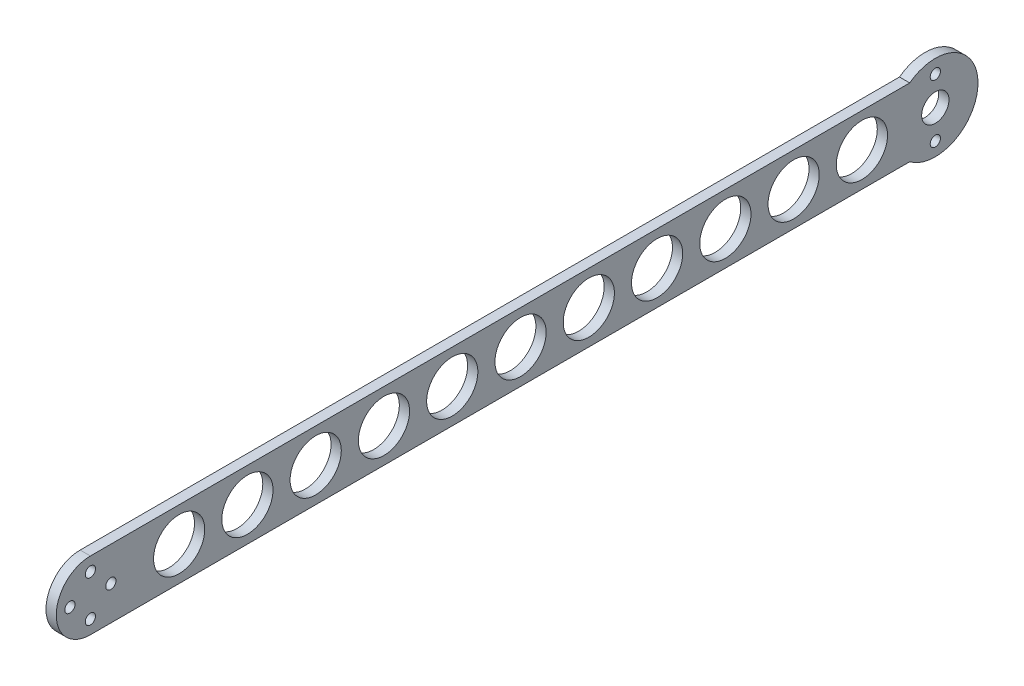
SolidWorks part; units mm, degrees
ref_plane "前视基准面" through (0, 0, 0) normal (0, 0, 1) x (1, 0, 0)
ref_plane "上视基准面" through (0, 0, 0) normal (0, 1, 0) x (1, 0, 0)
ref_plane "右视基准面" through (0, 0, 0) normal (1, 0, 0) x (0, 0, -1)
other "Configuration Table"
sketch "草图1" plane through (0, 0, 0) normal (1, 0, 0) x (0, 0, -1)
  line L5 (-120, 10) -> (120, 10)
  line L7 (-120, -10) -> (120, -10)
  line L9 (0, -10) -> (0, 10) construction
  line L10 (-120, 0) -> (127.5, 0) construction
  arc A1 (120, -10) -> (120, 10) centre (127.5, 0) ccw
  arc A2 (-120, 10) -> (-120, -10) centre (-120, 0) ccw
  point P0 (0, 0)
  point P1 (0, 0)
  point P5 (0, 0)
  dimension "D4" = 20
  dimension "D3" = 25
  dimension "D1" = 240
  dimension "D2" = 20
extrude "凸台-拉伸1" add sketch "草图1" along normal blind 3
sketch "草图2" plane through (3, 0, 0) normal (1, 0, 0) x (0, 0, -1)
  line L0 (120, 10) -> (-120, 10) construction
  circle A0 centre (-120, 0) radius 6 construction
  circle A1 centre (-120, 6) radius 1.5
  circle A2 centre (-114, 0) radius 1.5
  circle A3 centre (-120, -6) radius 1.5
  circle A4 centre (-126, 0) radius 1.5
  circle A5 centre (127.5, 0) radius 8.5 construction
  circle A7 centre (127.5, 8.5) radius 1.5
  circle A8 centre (127.5, -8.5) radius 1.5
  circle A9 centre (127.5, 0) radius 4
  dimension "D2" = 12
  dimension "D4" = 3
  dimension "D5" = 3
  dimension "D6" = 3
  dimension "D7" = 3
  dimension "D8" = 17
  dimension "D9" = 3
  dimension "D10" = 3
  dimension "D11" = 8
  dimension "D1" = 120
  dimension "D3" = 10
extrude "切除-拉伸1" cut sketch "草图2" against normal blind 3
sketch "草图4" plane through (3, 0, 0) normal (1, 0, 0) x (0, 0, -1)
  line L0 (120, 10) -> (-120, 10) construction
  circle A0 centre (-94, 0) radius 7.5
  circle A1 centre (-114, 0) radius 1.5 construction
  circle A2 centre (-74, 0) radius 7.5 construction
  circle A3 centre (-74, 0) radius 7.5
  circle A4 centre (-54, 0) radius 7.5
  circle A5 centre (-34, 0) radius 7.5
  circle A6 centre (-14, 0) radius 7.5
  circle A7 centre (6, 0) radius 7.5
  circle A8 centre (26, 0) radius 7.5
  circle A9 centre (46, 0) radius 7.5
  circle A10 centre (66, 0) radius 7.5
  circle A11 centre (86, 0) radius 7.5
  circle A12 centre (106, 0) radius 7.5
  dimension "D1" = 15
  dimension "D6" = 15
  dimension "D2" = 20
  dimension "D3" = 10
  dimension "D4" = 10
  dimension "D5" = 20
  dimension "D7" = 11
extrude "切除-拉伸2" cut sketch "草图4" against normal blind 250
